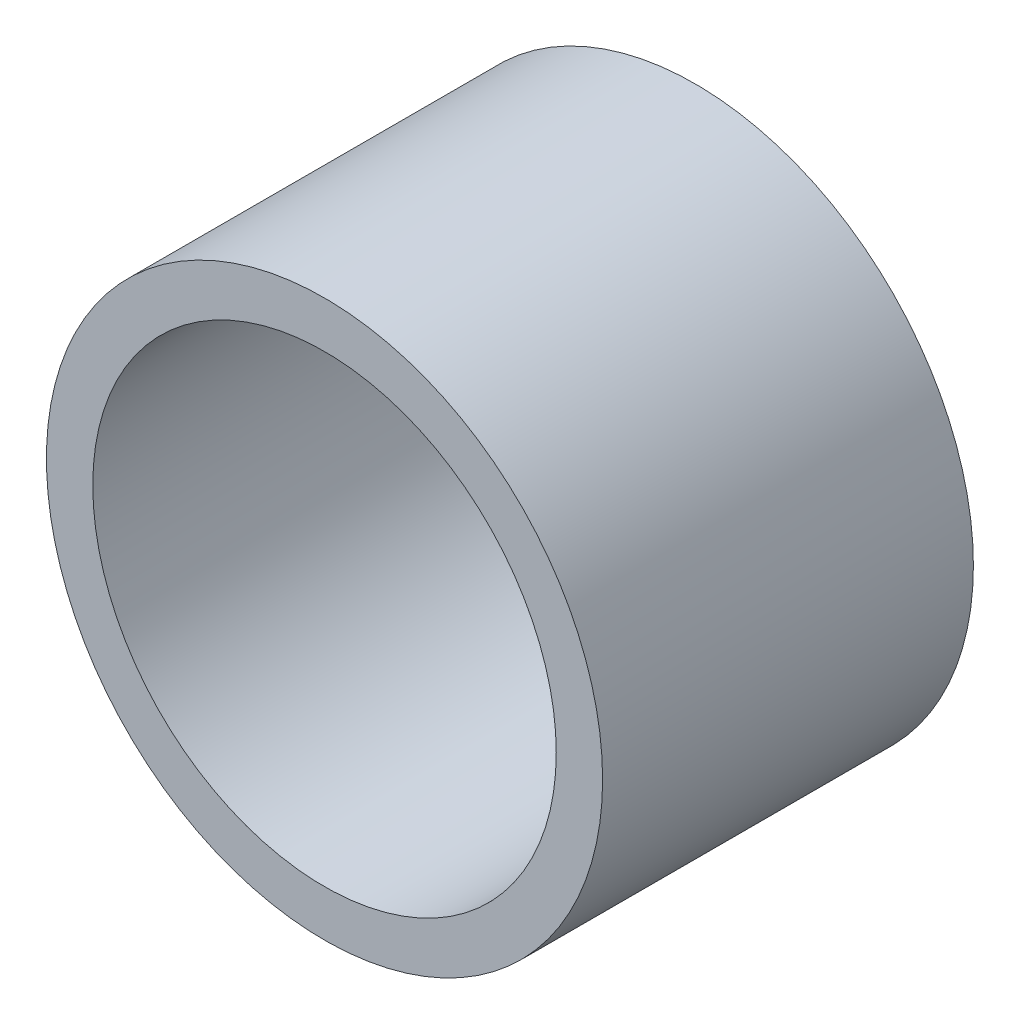
SolidWorks part; units mm, degrees
ref_plane "Alzado" through (0, 0, 0) normal (0, 0, 1) x (1, 0, 0)
ref_plane "Planta" through (0, 0, 0) normal (0, 1, 0) x (1, 0, 0)
ref_plane "Vista lateral" through (0, 0, 0) normal (1, 0, 0) x (0, 0, -1)
sketch "Croquis1" plane through (0, 0, 0) normal (0, 0, 1) x (1, 0, 0)
  circle A0 centre (0, 0) radius 3
  circle A1 centre (0, 0) radius 2.5
  dimension "D1" = 6
  dimension "D2" = 5
extrude "Saliente-Extruir1" add sketch "Croquis1" along normal blind 4
